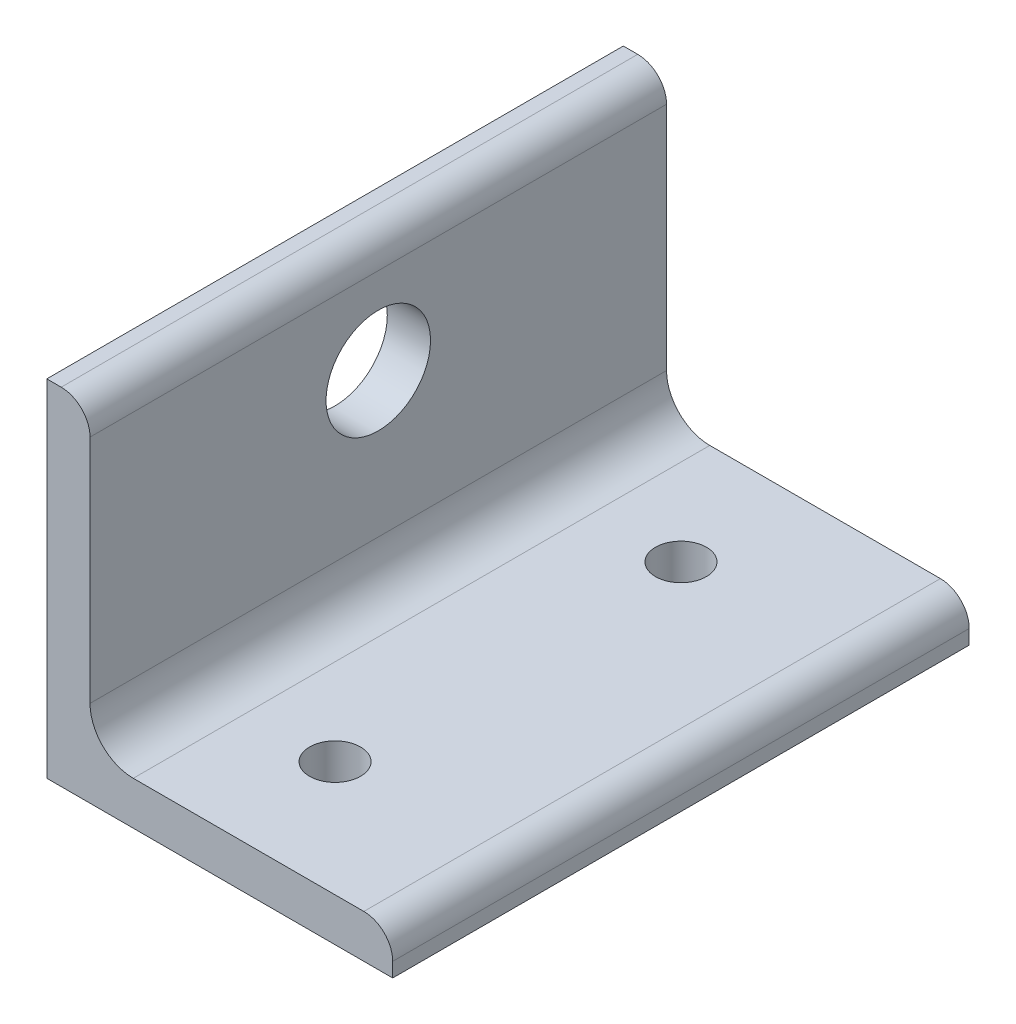
SolidWorks part; units mm, degrees
ref_plane "Front" through (0, 0, 0) normal (0, 0, 1) x (1, 0, 0)
ref_plane "Top" through (0, 0, 0) normal (0, 1, 0) x (1, 0, 0)
ref_plane "Right" through (0, 0, 0) normal (1, 0, 0) x (0, 0, -1)
sketch "Sketch1" plane through (0, 0, 0) normal (0, 0, 1) x (1, 0, 0)
  line L0 (0, 0) -> (0, 38.1)
  line L2 (0, 0) -> (38.1, 0)
  line L3 (34.925, 4.7625) -> (9.525, 4.7625)
  line L4 (4.7625, 34.925) -> (4.7625, 9.525)
  line L6 (0, 38.1) -> (1.5875, 38.1)
  line L7 (38.1, 0) -> (38.1, 1.5875)
  arc A0 (4.7625, 34.925) -> (1.5875, 38.1) centre (1.5875, 34.925) ccw
  arc A1 (4.7625, 9.525) -> (9.525, 4.7625) centre (9.525, 9.525) ccw
  arc A2 (38.1, 1.5875) -> (34.925, 4.7625) centre (34.925, 1.5875) ccw
extrude "Extrude1" add sketch "Sketch1" along normal blind 63.5
hole_wizard "#10 Clearance Hole1" positions "Sketch4" profile "Sketch3" hole size "#10" standard "Ansi Inch" end condition up to next
sketch "Sketch4" plane through (0, 4.7625, 0) normal (0, 1, 0) x (-1, 0, 0)
  line L0 (0, 63.5) -> (0, 0) construction
  line L1 (0, 0) -> (-38.1, 0) construction
  point P0 (-19.05, 50.8)
  point P1 (-19.05, 12.7)
  dimension "D1" = 19.05
  dimension "D2" = 12.7
  dimension "D3" = 38.1
sketch "Sketch3" plane through (19.05, 4.7625, 50.8) normal (1, 0, 0) x (0, 0, 1)
  line L0 (0, 0) -> (0, 4.7625)
  line L1 (0, 4.7625) -> (2.8067, 4.7625)
  line L2 (2.8067, 4.7625) -> (2.8067, 0)
  line L5 (2.8067, 0) -> (0, 0)
  line L11 (0, -6.35) -> (0, 107.95) construction
  dimension "Thru Hole Dia." = 5.6134
  dimension "Thru Hole Depth" = 4.7625
hole_wizard "7/16 Clearance Hole1" positions "Sketch6" profile "Sketch7" hole size "7/16" standard "Ansi Inch" end condition through all
sketch "Sketch6" plane through (4.7625, 0, 0) normal (1, 0, 0) x (0, 0, -1)
  line L0 (0, 38.1) -> (0, 0) construction
  line L1 (-63.5, 0) -> (0, 0) construction
  point P0 (-31.75, 25.4)
  dimension "D1" = 31.75
  dimension "D2" = 25.4
sketch "Sketch7" plane through (4.7625, 25.4, 31.75) normal (0, 1, 0) x (0, 0, -1)
  line L0 (0, 0) -> (0, 4.7625)
  line L1 (0, 4.7625) -> (5.7544, 4.7625)
  line L2 (5.7544, 4.7625) -> (5.7544, 0)
  line L5 (5.7544, 0) -> (0, 0)
  line L11 (0, -6.35) -> (0, 107.95) construction
  dimension "Thru Hole Dia." = 11.5087
  dimension "Thru Hole Depth" = 4.7625
